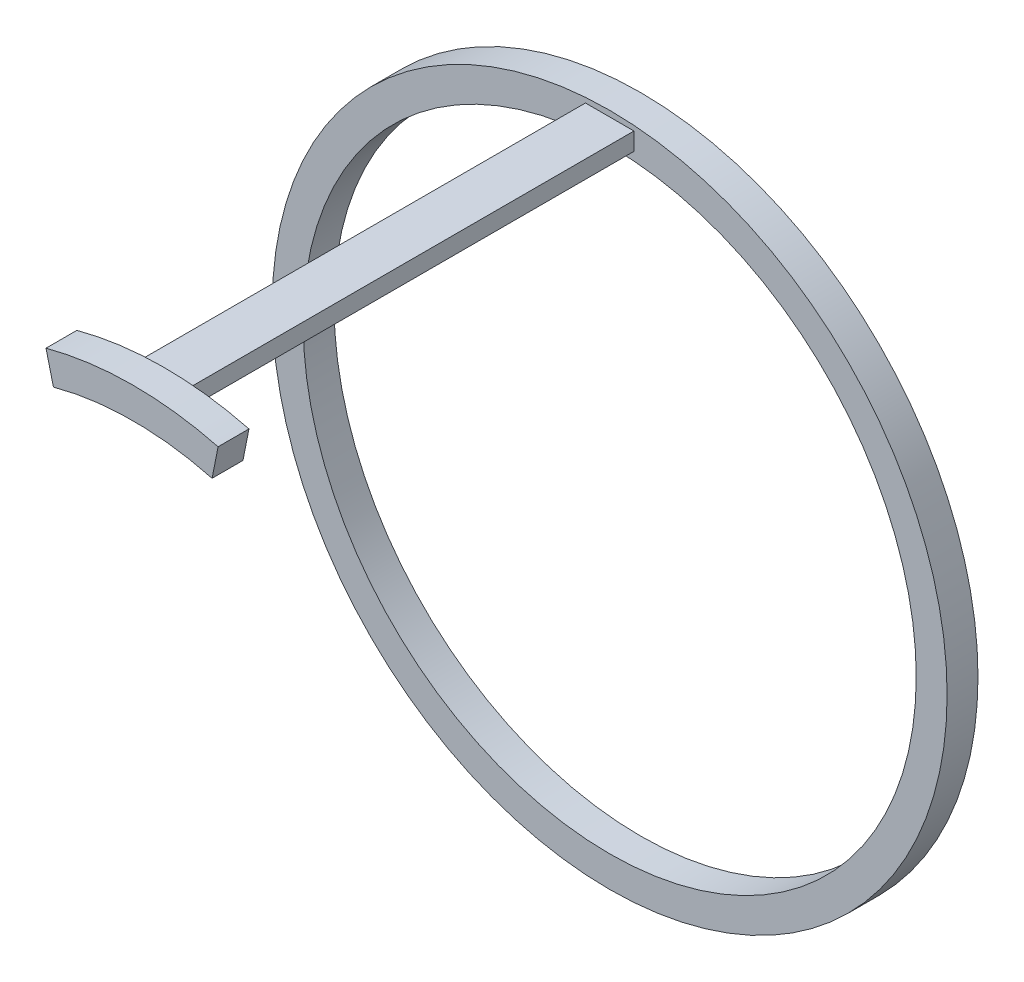
SolidWorks part; units mm, degrees
ref_plane "Front Plane" through (0, 0, 0) normal (0, 0, 1) x (1, 0, 0)
ref_plane "Top Plane" through (0, 0, 0) normal (0, 1, 0) x (1, 0, 0)
ref_plane "Right Plane" through (0, 0, 0) normal (1, 0, 0) x (0, 0, -1)
sketch "Sketch1" plane through (0, 0, 0) normal (0, 0, 1) x (1, 0, 0)
  circle A0 centre (0, 0) radius 69.5
  circle A1 centre (0, 0) radius 76.5
  dimension "D1" = 153
  dimension "D2" = 139
extrude "Boss-Extrude1" add sketch "Sketch1" along normal blind 7
sketch "Sketch2" plane through (0, 0, 7) normal (0, 0, 1) x (1, 0, 0)
  line L1 (-5.4992, 75.1847) -> (5.4992, 75.1847)
  line L2 (-5.4992, 75.1847) -> (-5.4992, 71.1885)
  line L3 (-5.4992, 71.1885) -> (5.4992, 71.1885)
  line L4 (5.4992, 75.1847) -> (5.4992, 71.1885)
  line L5 (-5.4992, 75.1847) -> (5.4992, 71.1885) construction
  line L6 (-5.4992, 71.1885) -> (5.4992, 75.1847) construction
  point P0 (0, 73.1866)
extrude "Boss-Extrude2" add sketch "Sketch2" along normal blind 101
sketch "Sketch3" plane through (0, 0, 108) normal (0, 0, 1) x (1, 0, 0)
  line L0 (-18.1199, 67.0963) -> (-19.8014, 73.8928)
  line L1 (17.8508, 67.1684) -> (19.2161, 74.0472)
  arc A0 (-18.1199, 67.0963) -> (17.8508, 67.1684) centre (0, 0) cw
  circle A1 centre (0, 0) radius 69.5 construction
  arc A2 (-19.8014, 73.8928) -> (19.2161, 74.0472) centre (0, 0) cw
  circle A3 centre (0, 0) radius 76.5 construction
extrude "Boss-Extrude3" add sketch "Sketch3" along normal blind 7
